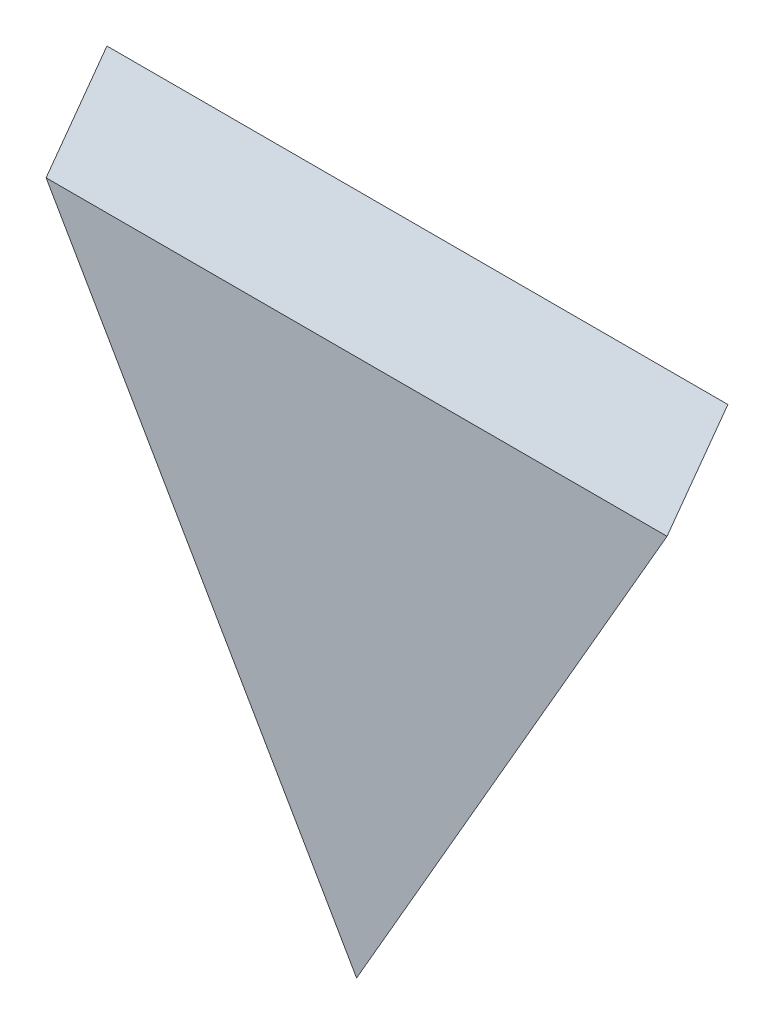
SolidWorks part; units mm, degrees
ref_plane "Front Plane" through (0, 0, 0) normal (0, 0, 1) x (1, 0, 0)
ref_plane "Top Plane" through (0, 0, 0) normal (0, 1, 0) x (1, 0, 0)
ref_plane "Right Plane" through (0, 0, 0) normal (1, 0, 0) x (0, 0, -1)
sketch "Sketch1" plane through (0, 0, 0) normal (0, 0, 1) x (1, 0, 0)
  line L0 (0, 0) -> (38.1, 65.9911)
  line L1 (38.1, 65.9911) -> (-38.1, 65.9911)
  line L2 (-38.1, 65.9911) -> (0, 0)
  dimension "D1" = 76.2
  dimension "D2" = 76.2
  dimension "D3" = 76.2
sketch "Sketch2" plane through (0, 0, 0) normal (1, 0, 0) x (0, 0, -1)
  line L0 (0, 57.5706) -> (7.4649, 67.8451)
  line L1 (0, 65.9911) -> (0, 0) construction
  line L4 (0, 57.5706) -> (27.1129, 57.5706) construction
  line L5 (0, 0) -> (32.3088, 0) construction
  line L6 (0, 0) -> (-32.6313, 23.7081) construction
  point P4 (0, -0.545)
  point P5 (-25.0372, 24.171)
  point P11 (-28.5208, 28.5208)
  point P12 (11.108, 72.0242)
  dimension "D1" = 12.7
  dimension "D2" = 46.5756
  dimension "D3" = 90
  dimension "D4" = 54
sweep "Sweep4" add profiles "Sketch1" path "Sketch2"
